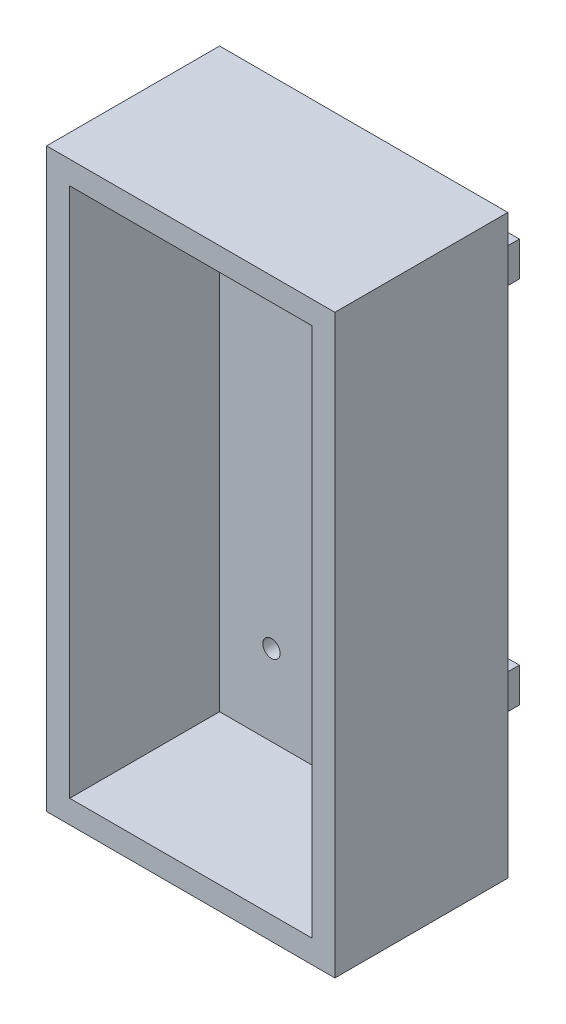
SolidWorks part; units mm, degrees
ref_plane "Front Plane" through (0, 0, 0) normal (0, 0, 1) x (1, 0, 0)
ref_plane "Top Plane" through (0, 0, 0) normal (0, 1, 0) x (1, 0, 0)
ref_plane "Right Plane" through (0, 0, 0) normal (1, 0, 0) x (0, 0, -1)
sketch "Sketch1" plane through (0, 0, 0) normal (0, 0, 1) x (1, 0, 0)
  line L1 (0, 0) -> (50, 0)
  line L2 (0, 0) -> (0, 100)
  line L3 (0, 100) -> (50, 100)
  line L4 (50, 0) -> (50, 100)
  dimension "D1" = 100
  dimension "D2" = 50
extrude "Boss-Extrude1" add sketch "Sketch1" along normal blind 30
sketch "Sketch2" plane through (0, 0, 30) normal (0, 0, 1) x (1, 0, 0)
  line L0 (50, 100) -> (0, 100) construction
  line L1 (4, 4) -> (46, 4)
  line L2 (4, 4) -> (4, 96)
  line L3 (4, 96) -> (46, 96)
  line L4 (46, 4) -> (46, 96)
  line L5 (0, 100) -> (0, 0) construction
  line L6 (50, 0) -> (50, 100) construction
  line L7 (0, 0) -> (50, 0) construction
  dimension "D1" = 4
  dimension "D2" = 4
  dimension "D3" = 4
  dimension "D4" = 4
extrude "Cut-Extrude1" cut sketch "Sketch2" against normal blind 26
sketch "Sketch3" plane through (0, 0, 0) normal (0, 0, -1) x (-1, 0, 0)
  line L0 (0, 0) -> (-50, 0) construction
  line L1 (-40, 21) -> (-10, 21)
  line L2 (-40, 21) -> (-40, 15)
  line L3 (-40, 15) -> (-10, 15)
  line L4 (-10, 21) -> (-10, 15)
  line L5 (-50, 50) -> (0, 50) construction
  line L6 (-50, 0) -> (-50, 100) construction
  line L7 (0, 100) -> (0, 0) construction
  line L8 (-40, 85) -> (-10, 85)
  line L9 (-10, 79) -> (-10, 85)
  line L10 (-40, 79) -> (-10, 79)
  line L11 (-40, 79) -> (-40, 85)
  point P6 (-25, 15)
  point P7 (-25, 0)
  dimension "D1" = 6
  dimension "D2" = 15
  dimension "D3" = 30
  dimension "D4" = 0
extrude "Boss-Extrude2" add sketch "Sketch3" along normal blind 24
sketch "Sketch4" plane through (0, 15, 0) normal (0, -1, 0) x (1, 0, 0)
  line L1 (40, -24) -> (40, 0) construction
  line L2 (40, -24) -> (10, -24) construction
  circle A0 centre (25, -12) radius 9
  dimension "D1" = 18
  dimension "D2" = 15
  dimension "D3" = 12
extrude "Cut-Extrude2" cut sketch "Sketch4" against normal through all both and the other way through all
sketch "Sketch5" plane through (0, 0, -24) normal (0, 0, -1) x (-1, 0, 0)
  line L0 (-40, 15) -> (-10, 15) construction
  line L2 (-10, 15) -> (-10, 21) construction
  line L3 (-10, 21) -> (-40, 21) construction
  line L4 (-40, 21) -> (-40, 15) construction
  line L5 (-10, 85) -> (-40, 85) construction
  line L6 (-10, 79) -> (-10, 85) construction
  line L7 (-40, 85) -> (-40, 79) construction
  line L8 (-40, 79) -> (-10, 79) construction
  circle A0 centre (-13, 18) radius 1.5
  circle A1 centre (-37, 18) radius 1.5
  circle A2 centre (-13, 82) radius 1.5
  circle A3 centre (-37, 82) radius 1.5
  point P10 (0, 0)
  point P12 (-10, 17.1061)
  dimension "D1" = 3
  dimension "D2" = 3
  dimension "D3" = 3
  dimension "D4" = 3
  dimension "D5" = 3
  dimension "D6" = 3
  dimension "D7" = 3
  dimension "D8" = 3
  dimension "D9" = 3
  dimension "D10" = 3
  dimension "D11" = 3
  dimension "D12" = 3
extrude "Cut-Extrude3" cut sketch "Sketch5" against normal through all both and the other way through all
sketch "Sketch6" plane through (0, 15, 0) normal (0, -1, 0) x (1, 0, 0)
  line L0 (40, -24) -> (40, 0) construction
  line L1 (10, -24) -> (40, -24)
  line L2 (10, -24) -> (10, -12)
  line L3 (10, -12) -> (40, -12)
  line L4 (40, -24) -> (40, -12)
extrude "Cut-Extrude4" cut sketch "Sketch6" against normal through all both and the other way through all
